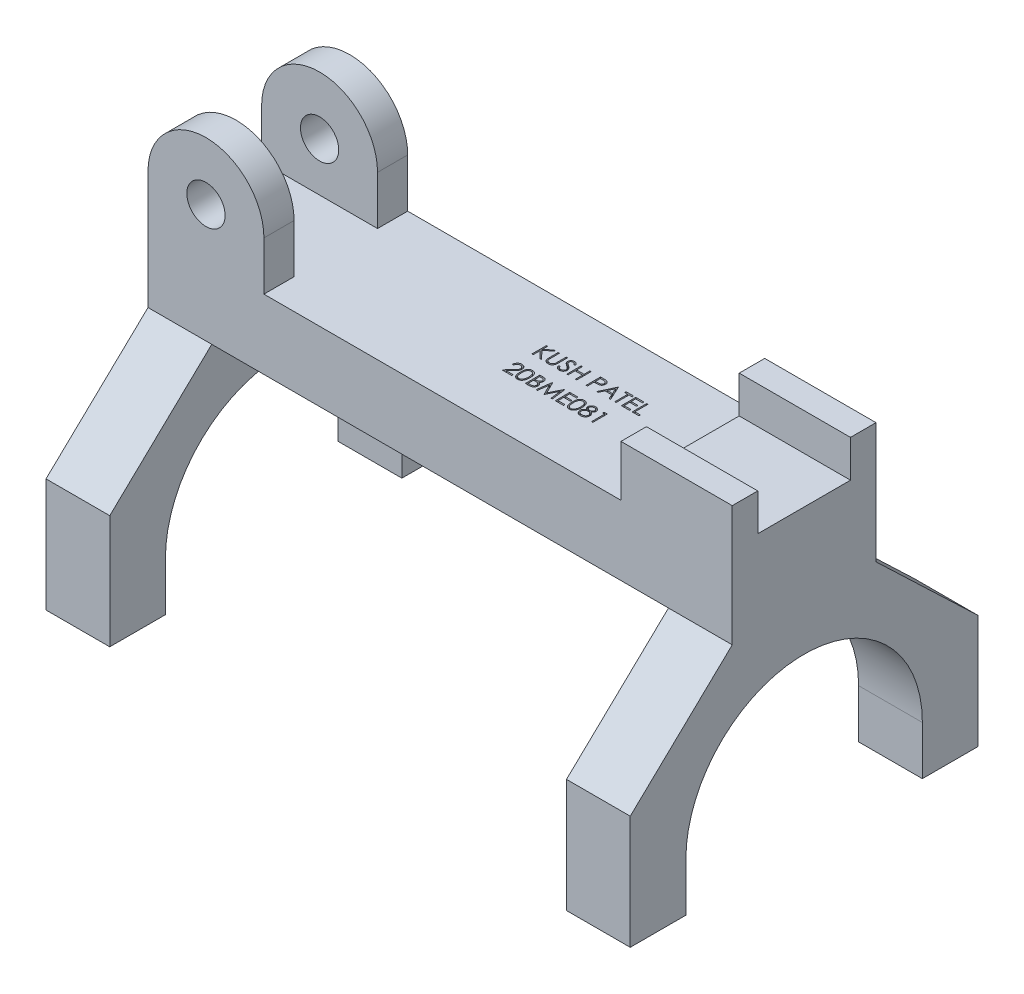
SolidWorks part; units mm, degrees
ref_plane "Front Plane" through (0, 0, 0) normal (0, 0, 1) x (1, 0, 0)
ref_plane "Top Plane" through (0, 0, 0) normal (0, 1, 0) x (1, 0, 0)
ref_plane "Right Plane" through (0, 0, 0) normal (1, 0, 0) x (0, 0, -1)
sketch "Sketch1" plane through (0, 0, 0) normal (0, 0, 1) x (1, 0, 0)
  line L0 (-58.8442, 0) -> (-58.8442, 46.228)
  line L1 (-44.8742, 0) -> (-44.8742, 46.228)
  line L2 (55.2018, 0) -> (55.2018, 46.228)
  line L3 (69.1718, 0) -> (69.1718, 46.228)
  line L4 (-58.8442, 0) -> (-44.8742, 0)
  line L5 (55.2018, 0) -> (69.1718, 0)
  line L6 (-58.8442, 46.228) -> (69.1718, 46.228)
  line L7 (-58.8442, 46.228) -> (-58.8442, 84.836)
  line L8 (69.1718, 46.228) -> (69.1718, 84.836)
  line L9 (69.1718, 84.836) -> (69.1718, 46.228)
  line L10 (-58.8442, 84.836) -> (69.1718, 84.836)
  point P0 (-58.8442, 0)
  point P1 (69.1718, 0)
  point P2 (-44.8742, 0)
  point P3 (55.2018, 0)
  dimension "D1" = 128.016
  dimension "D2" = 13.97
  dimension "D3" = 13.97
  dimension "D4" = 46.228
  dimension "D5" = 38.608
extrude "Boss-Extrude1" add sketch "Sketch1" along normal blind 76.2 contours L6 L0 L4 L1 | L6 L2 L5 L3
sketch "Sketch2" plane through (69.1718, 0, 0) normal (1, 0, 0) x (0, 0, -1)
  line L0 (-76.2, 0) -> (0, 0) construction
  line L3 (-64.008, 10.668) -> (-64.008, 0)
  line L4 (-12.192, 10.668) -> (-12.192, 0)
  line L5 (-64.008, 0) -> (-12.192, 0)
  arc A0 (-12.192, 10.668) -> (-64.008, 10.668) centre (-38.1, 10.668) ccw
  point P5 (-38.1, 0)
  dimension "D2" = 25.908
  dimension "D1" = 10.668
extrude "Cut-Extrude1" cut sketch "Sketch2" against normal blind 128.016
sketch "Sketch3" plane through (-58.8442, 0, 0) normal (-1, 0, 0) x (0, 0, 1)
  line L0 (38.1, 46.228) -> (53.848, 46.228)
  line L1 (76.2, 46.228) -> (0, 46.228) construction
  line L2 (38.1, 46.228) -> (22.352, 46.228)
  line L3 (76.2, 0) -> (76.2, 46.228) construction
  line L5 (76.2, 24.892) -> (53.848, 46.228)
  line L6 (22.352, 46.228) -> (0, 24.892)
  line L7 (0, 0) -> (0, 46.228) construction
  line L8 (22.352, 46.228) -> (0, 46.228)
  line L9 (0, 46.228) -> (0, 24.892)
  line L10 (53.848, 46.228) -> (76.2, 46.228)
  line L11 (76.2, 46.228) -> (76.2, 24.892)
  point P4 (76.2, 0)
  point P6 (76.2, 24.892)
  line M7 (76.2, 0) -> (76.2, 46.228)
  line M8 (76.2, 46.228) -> (0, 46.228)
  line M9 (0, 46.228) -> (0, 0)
  dimension "D1" = 15.748
  dimension "D2" = 15.748
  dimension "D3" = 24.892
extrude "Cut-Extrude2" cut sketch "Sketch3" against normal blind 128.016 contours L6 M8 M9 | L5 M7 M8
sketch "Sketch4" plane through (0, 46.228, 0) normal (0, 1, 0) x (1, 0, 0)
  line L0 (-58.8442, -22.352) -> (69.1718, -22.352)
  line L1 (69.1718, -22.352) -> (69.1718, -53.848)
  line L2 (69.1718, -53.848) -> (-58.8442, -53.848)
  line L3 (-58.8442, -53.848) -> (-58.8442, -22.352)
extrude "Boss-Extrude3" add sketch "Sketch4" along normal blind 15.24
sketch "Sketch5" plane through (0, 0, 53.848) normal (0, 0, 1) x (1, 0, 0)
  line L0 (-58.8442, 61.468) -> (-58.8442, 72.136)
  line L1 (-33.4442, 72.136) -> (-33.4442, 61.468)
  line L2 (-58.8442, 61.468) -> (69.1718, 61.468) construction
  line L3 (-58.8442, 61.468) -> (-33.4442, 61.468)
  arc A0 (-58.8442, 72.136) -> (-33.4442, 72.136) centre (-46.1442, 72.136) cw
  dimension "D2" = 12.7
  dimension "D1" = 10.668
extrude "Boss-Extrude4" add sketch "Sketch5" against normal blind 31.496
sketch "Sketch6" plane through (-58.8442, 0, 0) normal (-1, 0, 0) x (0, 0, 1)
  line L1 (47.244, 61.468) -> (28.956, 61.468)
  line L2 (22.352, 72.136) -> (22.352, 46.228) construction
  line L5 (28.956, 61.468) -> (28.956, 87.5272)
  line L6 (28.956, 87.5272) -> (47.244, 87.5272)
  line L7 (47.244, 87.5272) -> (47.244, 61.468)
  dimension "D1" = 18.288
  dimension "D2" = 6.604
  dimension "D3" = 0
extrude "Cut-Extrude3" cut sketch "Sketch6" against normal blind 42.164
sketch "Sketch7" plane through (0, 61.468, 0) normal (0, 1, 0) x (1, 0, 0)
  line L0 (-33.4442, -53.848) -> (69.1718, -53.848) construction
  line L1 (69.1718, -22.352) -> (44.7878, -22.352)
  line L2 (69.1718, -22.352) -> (69.1718, -53.848)
  line L3 (69.1718, -53.848) -> (44.7878, -53.848)
  line L4 (44.7878, -22.352) -> (44.7878, -53.848)
  dimension "D1" = 24.384
extrude "Boss-Extrude5" add sketch "Sketch7" along normal blind 3.048
sketch "Sketch8" plane through (0, 64.516, 0) normal (0, 1, 0) x (1, 0, 0)
  line L0 (44.7878, -22.352) -> (44.7878, -53.848) construction
  line L1 (69.1718, -53.848) -> (44.7878, -53.848)
  line L2 (69.1718, -53.848) -> (69.1718, -48.26)
  line L3 (69.1718, -48.26) -> (44.7878, -48.26)
  line L4 (44.7878, -53.848) -> (44.7878, -48.26)
  line L6 (69.1718, -22.352) -> (44.7878, -22.352)
  line L7 (69.1718, -22.352) -> (69.1718, -27.94)
  line L8 (69.1718, -27.94) -> (44.7878, -27.94)
  line L9 (44.7878, -22.352) -> (44.7878, -27.94)
  dimension "D1" = 5.588
  dimension "D2" = 5.588
extrude "Boss-Extrude6" add sketch "Sketch8" along normal blind 8.128
sketch "Sketch9" plane through (0, 0, 53.848) normal (0, 0, 1) x (1, 0, 0)
  circle A0 centre (-46.1442, 72.136) radius 4.191
  dimension "D1" = 8.382
extrude "Cut-Extrude4" cut sketch "Sketch9" against normal blind 31.496
sketch "Sketch10" plane through (0, 61.468, 0) normal (0, 1, 0) x (1, 0, 0)
  text T0 "\r\n\r\nKUSH PATEL \r\n20BME081"
extrude "Cut-Extrude5" cut sketch "Sketch10" against normal blind 2.54
